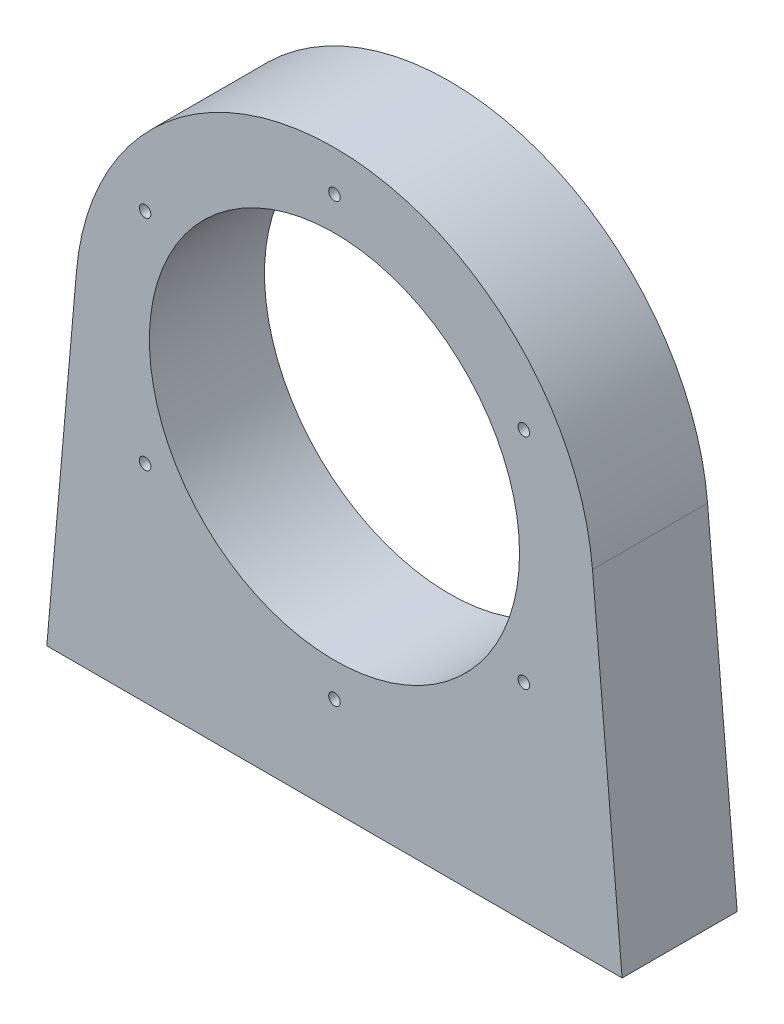
SolidWorks part; units mm, degrees
ref_plane "前视基准面" through (0, 0, 0) normal (0, 0, 1) x (1, 0, 0)
ref_plane "上视基准面" through (0, 0, 0) normal (0, 1, 0) x (1, 0, 0)
ref_plane "右视基准面" through (0, 0, 0) normal (1, 0, 0) x (0, 0, -1)
sketch "草图1" plane through (0, 0, 0) normal (0, 0, 1) x (1, 0, 0)
  line L0 (0, 0) -> (150, 0)
  line L1 (150, 0) -> (142.2732, 88.3533)
  line L2 (0, 0) -> (7.7268, 88.3533)
  line L3 (75, 0) -> (75, 150)
  arc A0 (7.7268, 88.3533) -> (142.2732, 88.3533) centre (75, 82.47) cw
  circle A3 centre (75, 82.47) radius 48.25
  dimension "D1" = 150
  dimension "D3" = 96.5
  dimension "D2" = 150
extrude "凸台-拉伸1" add sketch "草图1" along normal blind 30 contours A3 L3 A0 L2 L0 | A3 L3 L0 L1 A0
sketch "草图2" plane through (0, 0, 30) normal (0, 0, 1) x (1, 0, 0)
  circle A0 centre (75, 82.47) radius 48.25 construction
  circle A3 centre (75, 139.47) radius 1.5
  circle A4 centre (124.3634, 110.97) radius 1.5
  circle A5 centre (124.3634, 53.97) radius 1.5
  circle A6 centre (75, 25.47) radius 1.5
  circle A7 centre (25.6366, 53.97) radius 1.5
  circle A8 centre (25.6366, 110.97) radius 1.5
  point P18 (75, 82.47)
  dimension "D2" = 3
  dimension "D3" = 6
extrude "切除-拉伸1" cut sketch "草图2" against normal up to next
